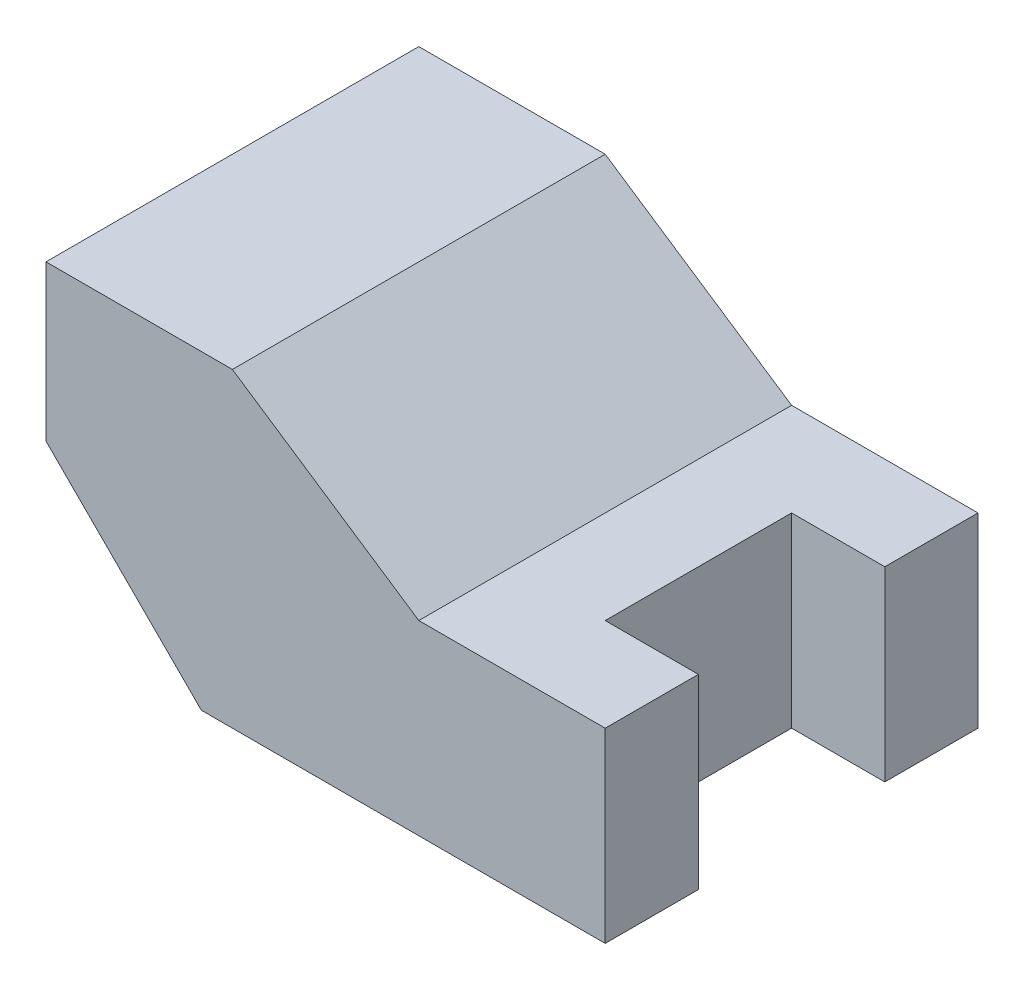
SolidWorks part; units mm, degrees
ref_plane "Front Plane" through (0, 0, 0) normal (0, 0, 1) x (1, 0, 0)
ref_plane "Top Plane" through (0, 0, 0) normal (0, 1, 0) x (1, 0, 0)
ref_plane "Right Plane" through (0, 0, 0) normal (1, 0, 0) x (0, 0, -1)
sketch "Sketch1" plane through (0, 0, 0) normal (0, 0, 1) x (1, 0, 0)
  line L1 (-1143, -635) -> (1143, -635)
  line L2 (-1143, -635) -> (-1143, 635)
  line L3 (-1143, 635) -> (1143, 635)
  line L4 (1143, -635) -> (1143, 635)
  line L5 (-1143, -635) -> (1143, 635) construction
  line L6 (-1143, 635) -> (1143, -635) construction
  point P0 (0, 0)
  dimension "D1" = 1270
  dimension "D2" = 2286
extrude "Boss-Extrude1" add sketch "Sketch1" along normal blind 1524
sketch "Sketch2" plane through (0, 0, 1524) normal (0, 0, 1) x (1, 0, 0)
  line L0 (-1143, 0) -> (-508, -635)
  line L1 (-1143, 635) -> (-1143, -635) construction
  line L2 (-1143, -635) -> (1143, -635) construction
  line L3 (-508, -635) -> (-1143, -635)
  line L4 (-1143, -635) -> (-1143, 0)
  dimension "D1" = 635
  dimension "D2" = 635
extrude "Cut-Extrude1" cut sketch "Sketch2" against normal through all
sketch "Sketch3" plane through (0, 0, 1524) normal (0, 0, 1) x (1, 0, 0)
  line L0 (381, 127) -> (-381, 635)
  line L1 (1143, 635) -> (381, 635)
  line L2 (1143, 635) -> (1143, 127)
  line L3 (1143, 127) -> (381, 127)
  line L5 (1143, 635) -> (-1143, 635) construction
  line L6 (-381, 635) -> (381, 635)
  dimension "D1" = 762
  dimension "D2" = 508
  dimension "D3" = 762
extrude "Cut-Extrude2" cut sketch "Sketch3" against normal blind 1524
sketch "Sketch4" plane through (0, 127, 0) normal (0, 1, 0) x (1, 0, 0)
  line L0 (1143, 0) -> (1143, -1524) construction
  line L1 (1143, -1143) -> (762, -1143)
  line L2 (1143, -1143) -> (1143, -381)
  line L3 (1143, -381) -> (762, -381)
  line L4 (762, -1143) -> (762, -381)
  line L5 (381, -1524) -> (1143, -1524) construction
  dimension "D1" = 381
  dimension "D2" = 762
  dimension "D3" = 381
extrude "Cut-Extrude3" cut sketch "Sketch4" against normal blind 1524
